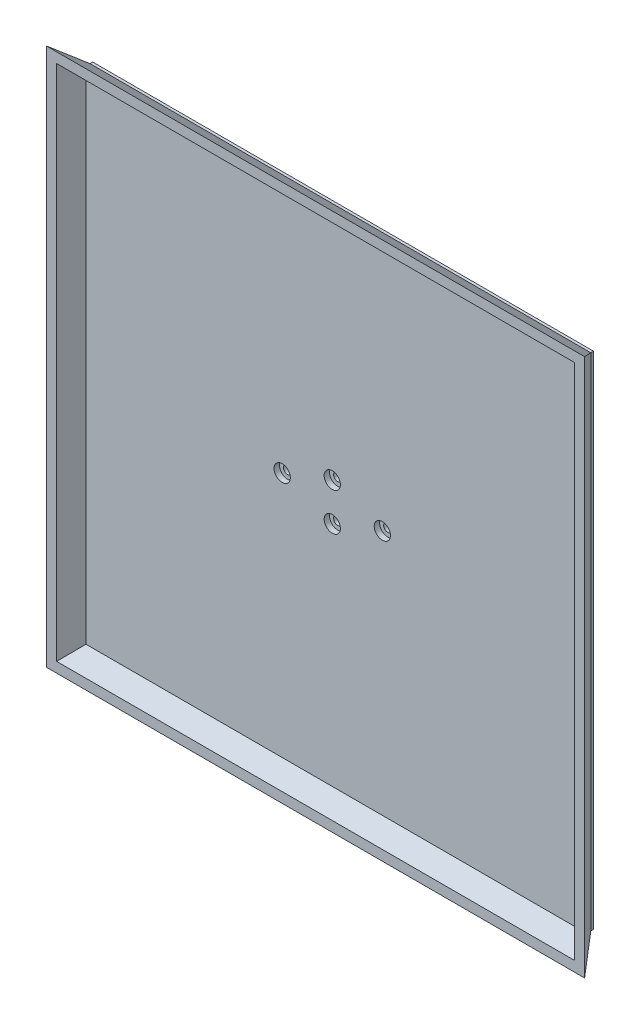
SolidWorks part; units mm, degrees
ref_plane "前视基准面" through (0, 0, 0) normal (0, 0, 1) x (1, 0, 0)
ref_plane "上视基准面" through (0, 0, 0) normal (0, 1, 0) x (1, 0, 0)
ref_plane "右视基准面" through (0, 0, 0) normal (1, 0, 0) x (0, 0, -1)
other "Configuration Table"
sketch "草图1" plane through (0, 0, 0) normal (0, 0, 1) x (1, 0, 0)
  line L11 (-17.5, -167.5) -> (167.5, -167.5)
  line L12 (-17.5, -167.5) -> (-17.5, 17.5)
  line L13 (-17.5, 17.5) -> (167.5, 17.5)
  line L14 (167.5, -167.5) -> (167.5, 17.5)
sketch "草图3" plane through (0, 0, 20) normal (0, 0, 1) x (1, 0, 0)
  line L7 (-32.4602, 32.2748) -> (182.5398, 32.2748)
  line L8 (-32.4602, 32.2748) -> (-32.4602, -182.7252)
  line L9 (-32.4602, -182.7252) -> (182.5398, -182.7252)
  line L10 (182.5398, 32.2748) -> (182.5398, -182.7252)
  point P12 (75.0398, -75.2252)
  dimension "D1" = 215
  dimension "D2" = 215
loft "放样1" add profiles "草图3", "草图1"
shell "抽壳2" thickness 3
sketch "草图4" plane through (0, 0, 3) normal (0, 0, 1) x (1, 0, 0)
  line L0 (75, 15.9864) -> (75, -182.7252)
  line L1 (166.0024, 15.9864) -> (-15.9976, 15.9864) construction
  line L2 (-32.4602, -182.7252) -> (182.5398, -182.7252) construction
  line L3 (-32.4602, -75.2252) -> (182.5398, -75.2252)
  line L4 (-32.4602, 32.2748) -> (-32.4602, -182.7252) construction
  line L5 (182.5398, -182.7252) -> (182.5398, 32.2748) construction
  circle A0 centre (66.25, -75.2252) radius 7 construction
  circle A1 centre (66.25, -75.2252) radius 4
  circle A2 centre (66.25, -68.2252) radius 1.5
  circle A3 centre (66.25, -82.2252) radius 1.5
  circle A4 centre (73.25, -75.2252) radius 1.5
  circle A5 centre (59.25, -75.2252) radius 1.5
  circle A6 centre (84.75, -75.2252) radius 1.5
  circle A7 centre (47.75, -75.2252) radius 1.5
  dimension "D1" = 8
  dimension "D2" = 14
  dimension "D3" = 3
  dimension "D4" = 3
  dimension "D5" = 3
  dimension "D6" = 3
  dimension "D7" = 3
  dimension "D8" = 3
  dimension "D9" = 37
  dimension "D10" = 18.5
extrude "切除-拉伸1" cut sketch "草图4" against normal blind 10 contours L3 A6 | L3 A6 | A3 | L3 A4 | L3 A4 | A2 | L3 A5 | L3 A5 | L3 A7 | L3 A7
sketch "草图6" plane through (0, 0, 3) normal (0, 0, 1) x (1, 0, 0)
  line L2 (38.15, -62.5) -> (34.15, -62.5)
  line L5 (38.15, -75) -> (38.15, -62.5)
  line L6 (38.15, -75) -> (38.15, -87.5)
  line L7 (94.35, -75) -> (94.35, -62.5)
  line L8 (94.35, -75) -> (94.35, -87.5)
  line L9 (94.35, -62.5) -> (98.35, -62.5)
  line L11 (98.35, -87.5) -> (94.35, -87.5)
  line L12 (98.35, -87.5) -> (101.35, -87.5)
  line L13 (101.35, -87.5) -> (101.35, -84.5)
  line L14 (98.35, -62.5) -> (101.35, -62.5)
  line L15 (101.35, -62.5) -> (101.35, -65.5)
  line L16 (38.15, -87.5) -> (34.15, -87.5)
  line L17 (34.15, -62.5) -> (31.15, -62.5)
  line L18 (31.15, -62.5) -> (31.15, -65.5)
  line L19 (34.15, -87.5) -> (31.15, -87.5)
  line L20 (31.15, -87.5) -> (31.15, -84.5)
  line L21 (31.15, -65.5) -> (34.15, -65.5)
  line L22 (31.15, -84.5) -> (34.15, -84.5)
  line L23 (34.15, -84.5) -> (34.15, -65.5)
  line L24 (101.35, -65.5) -> (98.35, -65.5)
  line L25 (101.35, -84.5) -> (98.35, -84.5)
  line L26 (98.35, -84.5) -> (98.35, -65.5)
extrude "凸台-拉伸1" add sketch "草图6" against normal blind 40.5
sketch "草图7" plane through (98.35, 0, 0) normal (1, 0, 0) x (0, 0, -1)
  line L0 (0, -65.5) -> (0, -84.5)
  line L1 (0, -75) -> (16.5, -75)
  line L2 (16.5, -75) -> (33.5, -75)
  line L3 (33.5, -75) -> (37.5, -75)
  line L4 (37.5, -84.5) -> (37.5, -65.5) construction
  circle A0 centre (16.5, -75) radius 1.51
  circle A1 centre (33.5, -75) radius 1.51
extrude "切除-拉伸2" cut sketch "草图7" against normal blind 100 contours L2 A0 L1 | L1 A0 L2 | L3 A1 L2 | L2 A1 L3
sketch "草图8" plane through (0, 0, 3) normal (0, 0, 1) x (1, 0, 0)
  circle A0 centre (66.25, -68.2252) radius 1.5
  circle A1 centre (59.25, -75.2252) radius 1.5
  circle A2 centre (47.75, -75.2252) radius 1.5
  circle A3 centre (73.25, -75.2252) radius 1.5
  circle A4 centre (84.75, -75.2252) radius 1.5
  circle A5 centre (66.25, -82.2252) radius 1.5
extrude "凸台-拉伸2" add sketch "草图8" against normal blind 3 contours A0
sketch "草图9" plane through (0, 0, 0) normal (0, 0, -1) x (-1, 0, 0)
  line L3 (-73.5858, -76.4142) -> (0, -2.8284)
  line L4 (17.5, 17.5) -> (17.5, -167.5) construction
  line L5 (0, -2.8284) -> (0, 0)
  line L6 (-72.7486, -69.9202) -> (-2.8284, 0)
  line L7 (-167.5, 17.5) -> (17.5, 17.5) construction
  line L8 (-2.8284, 0) -> (0, 0)
  line L9 (-72.7486, -69.9202) -> (-150, -147.1716)
  line L10 (-167.5, -167.5) -> (-167.5, 17.5) construction
  line L11 (-150, -147.1716) -> (-150, -150)
  line L12 (-73.5858, -76.4142) -> (-147.1716, -150)
  line L14 (17.5, -167.5) -> (-167.5, -167.5) construction
  line L15 (-147.1716, -150) -> (-150, -150)
extrude "凸台-拉伸3" add sketch "草图9" along normal blind 4 contours L9 L11 L15 L12 L3 L5 L8 L6
sketch "草图10" plane through (0, 0, 0) normal (0, 0, -1) x (-1, 0, 0)
  line L3 (-106.6693, -40.5023) -> (-147.1716, 17.5)
  line L4 (-167.5, 17.5) -> (17.5, 17.5) construction
  line L5 (-147.1716, 17.5) -> (-167.5, 17.5)
  line L6 (-121.9738, -30.8546) -> (-167.5, 34.3423)
  line L7 (-167.5, -167.5) -> (-167.5, 17.5) construction
  line L8 (-167.5, 34.3423) -> (-167.5, 17.5)
  line L9 (-106.6693, -40.5023) -> (17.5, -218.322)
  line L10 (17.5, 17.5) -> (17.5, -167.5) construction
  line L11 (17.5, -218.322) -> (17.5, -167.5)
  line L12 (-121.9738, -30.8546) -> (-26.556, -167.5)
  line L13 (17.5, -167.5) -> (-167.5, -167.5) construction
  line L14 (-26.556, -167.5) -> (17.5, -167.5)
extrude "凸台-拉伸4" add sketch "草图10" along normal blind 4 contours L3 L5 L8 L6 L12 L14 L11 L9
sketch "草图11" plane through (0, 0, -4) normal (0, 0, -1) x (-1, 0, 0)
  line L1 (-94.35, -62.5) -> (-38.15, -62.5)
  line L2 (-94.35, -62.5) -> (-94.35, -87.5)
  line L3 (-94.35, -87.5) -> (-38.15, -87.5)
  line L4 (-38.15, -62.5) -> (-38.15, -87.5)
extrude "切除-拉伸3" cut sketch "草图11" against normal blind 4 contours L2 L1 L4 L3
sketch "草图12" plane through (0, 0, 20) normal (0, 0, 1) x (1, 0, 0)
  line L1 (182.5398, 32.2748) -> (185.5398, 32.2748)
  line L2 (182.5398, 32.2748) -> (182.5398, -182.7252)
  line L3 (182.5398, -182.7252) -> (185.5398, -182.7252)
  line L4 (185.5398, 32.2748) -> (185.5398, -182.7252)
extrude "凸台-拉伸5" add sketch "草图12" against normal blind 10 separate body
sketch "草图13" plane through (185.5398, 0, 0) normal (1, 0, 0) x (0, 0, -1)
  line L0 (-10, -182.7252) -> (-10, 32.2748) construction
  line L1 (-20, 32.2748) -> (-10, 32.2748)
  line L2 (-20, 32.2748) -> (-20, -182.7252)
  line L3 (-20, -182.7252) -> (-10, -182.7252)
  line L4 (-10, 32.2748) -> (-10, -182.7252)
extrude "切除-拉伸4" cut sketch "草图13" against normal blind 300
sketch "草图15" plane through (0, 0, -4) normal (0, 0, -1) x (-1, 0, 0)
  line L1 (-154.8521, -152.6743) -> (-38.15, -152.6743)
  line L2 (-154.8521, -152.6743) -> (-154.8521, -87.5)
  line L3 (-154.8521, -87.5) -> (-38.15, -87.5)
  line L4 (-38.15, -152.6743) -> (-38.15, -87.5)
  line L5 (-94.35, -62.5) -> (17.5, -62.5)
  line L6 (-94.35, -62.5) -> (-94.35, 17.5)
  line L7 (-94.35, 17.5) -> (17.5, 17.5)
  line L8 (17.5, -62.5) -> (17.5, 17.5)
extrude "切除-拉伸5" cut sketch "草图15" against normal blind 4 contours L6 L5 L8 L7 | L2 L1 L4 L3
sketch "草图16" plane through (0, 0, 0) normal (0, 0, -1) x (-1, 0, 0)
  line L3 (-123.7693, -120.9409) -> (-167.5, -164.6716)
  line L4 (-134.8709, -12.3007) -> (-164.6716, 17.5)
  line L5 (-167.5, 17.5) -> (17.5, 17.5) construction
  line L6 (-164.6716, 17.5) -> (-167.5, 17.5)
  line L7 (-140.0326, -12.7959) -> (-167.5, 14.6716)
  line L8 (-167.5, -167.5) -> (-167.5, 17.5) construction
  line L9 (-167.5, 14.6716) -> (-167.5, 17.5)
  line L10 (-140.0326, -12.7959) -> (14.6716, -167.5)
  line L11 (17.5, -167.5) -> (-167.5, -167.5) construction
  line L12 (14.6716, -167.5) -> (17.5, -167.5)
  line L14 (-134.8709, -12.3007) -> (17.5, -164.6716)
  line L15 (17.5, 17.5) -> (17.5, -167.5) construction
  line L16 (17.5, -164.6716) -> (17.5, -167.5)
  line L17 (-167.5, -164.6716) -> (-167.5, -167.5)
  line L18 (-116.3532, -119.1816) -> (-164.6716, -167.5)
  line L19 (-164.6716, -167.5) -> (-167.5, -167.5)
  line L20 (-116.3532, -119.1816) -> (17.5, 14.6716)
  line L21 (17.5, 14.6716) -> (17.5, 17.5)
  line L22 (-123.7693, -120.9409) -> (14.6716, 17.5)
  line L23 (14.6716, 17.5) -> (17.5, 17.5)
extrude "凸台-拉伸6" add sketch "草图16" along normal blind 4
sketch "草图17" plane through (0, 0, 0) normal (0, 0, -1) x (-1, 0, 0)
  line L1 (-94.35, -62.5) -> (-38.15, -62.5)
  line L2 (-94.35, -62.5) -> (-94.35, -87.5)
  line L3 (-94.35, -87.5) -> (-38.15, -87.5)
  line L4 (-38.15, -62.5) -> (-38.15, -87.5)
extrude "切除-拉伸6" cut sketch "草图17" along normal blind 4 contours L2 L1 L4 L3
sketch "草图18" plane through (0, 0, 0) normal (0, 0, -1) x (-1, 0, 0)
  line L3 (-75, -119.25) -> (-33.5784, -119.25)
  line L7 (-65.3284, -87.5) -> (14.6716, -167.5) construction
  line L8 (-33.5784, -119.25) -> (-31.5784, -121.25)
  line L9 (-65.3284, -87.5) -> (14.6716, -167.5) construction
  line L10 (-75, -123.25) -> (-29.5784, -123.25)
  line L11 (-29.5784, -123.25) -> (-31.5784, -121.25)
  line L12 (-75, -119.25) -> (-116.4216, -119.25)
  line L13 (-164.6716, -167.5) -> (-84.6716, -87.5) construction
  line L14 (-75, -123.25) -> (-120.4216, -123.25)
  line L15 (-120.4216, -123.25) -> (-116.4216, -119.25)
  line L18 (-119.25, -75) -> (-119.25, -116.4216)
  line L19 (-90.3284, -87.5) -> (-167.5, -164.6716) construction
  line L20 (-119.25, -116.4216) -> (-121.25, -118.4216)
  line L21 (-123.25, -75) -> (-123.25, -120.4216)
  line L22 (-123.25, -120.4216) -> (-121.25, -118.4216)
  line L23 (-119.25, -75) -> (-119.25, -33.5784)
  line L24 (-167.5, 14.6716) -> (-90.3284, -62.5) construction
  line L25 (-123.25, -75) -> (-123.25, -29.5784)
  line L26 (-167.5, 14.6716) -> (-90.3284, -62.5) construction
  line L27 (-123.25, -29.5784) -> (-119.25, -33.5784)
  line L30 (-75, -30.75) -> (-116.4216, -30.75)
  line L31 (-164.6716, 17.5) -> (-84.6716, -62.5) construction
  line L32 (-75, -26.75) -> (-120.4216, -26.75)
  line L33 (-164.6716, 17.5) -> (-84.6716, -62.5) construction
  line L34 (-120.4216, -26.75) -> (-116.4216, -30.75)
  line L35 (-75, -30.75) -> (-33.5784, -30.75)
  line L36 (14.6716, 17.5) -> (-65.3284, -62.5) construction
  line L37 (-75, -26.75) -> (-29.5784, -26.75)
  line L38 (-65.3284, -62.5) -> (14.6716, 17.5) construction
  line L39 (-29.5784, -26.75) -> (-33.5784, -30.75)
  line L40 (-30.75, -33.5784) -> (-26.75, -29.5784)
  line L42 (-26.75, -75) -> (-26.75, -29.5784)
  line L43 (-59.6716, -62.5) -> (17.5, 14.6716) construction
  line L44 (-30.75, -75) -> (-30.75, -33.5784)
  line L45 (-30.75, -75) -> (-30.75, -116.4216)
  line L46 (-59.6716, -87.5) -> (17.5, -164.6716) construction
  line L47 (-26.75, -75) -> (-26.75, -120.4216)
  line L48 (-30.75, -116.4216) -> (-26.75, -120.4216)
extrude "凸台-拉伸7" add sketch "草图18" along normal blind 4
sketch "草图20" plane through (0, 0, 0) normal (0, 0, -1) x (-1, 0, 0)
  line L0 (-94.35, -62.5) -> (-94.35, -87.5)
  line L1 (-94.35, -87.5) -> (-38.15, -87.5)
  line L2 (-38.15, -87.5) -> (-38.15, -62.5)
  line L3 (-38.15, -62.5) -> (-94.35, -62.5)
  line L4 (-66.25, -75) -> (-66.25, -82)
  line L5 (-66.25, -75) -> (-47.75, -75)
  line L6 (-66.25, -75) -> (-84.75, -75)
  line L7 (-66.25, -75) -> (-66.25, -68)
  circle A0 centre (-84.75, -75) radius 1.5
  circle A1 centre (-47.75, -75) radius 1.5
  circle A2 centre (-66.25, -68) radius 1.5
  circle A3 centre (-66.25, -82) radius 1.5
extrude "切除-拉伸7" cut sketch "草图20" against normal blind 10
sketch "草图21" plane through (0, 0, -37.5) normal (0, 0, -1) x (-1, 0, 0)
  line L1 (-167.5, 17.5) -> (17.5, 17.5)
  line L2 (-167.5, 17.5) -> (-167.5, -167.5)
  line L3 (-167.5, -167.5) -> (17.5, -167.5)
  line L4 (17.5, 17.5) -> (17.5, -167.5)
extrude "切除-拉伸8" cut sketch "草图21" against normal blind 37.5
sketch "草图22" plane through (0, 0, 0) normal (0, 0, -1) x (-1, 0, 0)
  line L1 (17.5, 17.5) -> (-167.5, 17.5)
  line L2 (17.5, 17.5) -> (17.5, -167.5)
  line L3 (17.5, -167.5) -> (-167.5, -167.5)
  line L4 (-167.5, 17.5) -> (-167.5, -167.5)
  circle A0 centre (-66.25, -68) radius 1.5
  circle A1 centre (-66.25, -82) radius 1.5
  circle A2 centre (-84.75, -75) radius 1.5
  circle A3 centre (-47.75, -75) radius 1.5
extrude "凸台-拉伸8" add sketch "草图22" along normal blind 1 contours L2 L1 L4 L3 | A3 | A0 | A2 | A1
sketch "草图24" plane through (0, 0, 3) normal (0, 0, 1) x (1, 0, 0)
  circle A0 centre (66.25, -68) radius 3
  circle A1 centre (66.25, -82) radius 3
  circle A2 centre (47.75, -75) radius 3
  circle A3 centre (84.75, -75) radius 3
  circle M4 centre (66.25, -68) radius 1.5
  circle M5 centre (84.75, -75) radius 1.5
  circle M6 centre (66.25, -82) radius 1.5
extrude "切除-拉伸9" cut sketch "草图24" against normal blind 2 contours A0 M4 | A1 M6 | A3 M5 | A2
sketch "草图25" plane through (0, 0, -1) normal (0, 0, -1) x (-1, 0, 0)
  line L0 (-167.5, 17.5) -> (17.5, -167.5)
  line L1 (-75, -75) -> (-75, -68)
  line L2 (-75, -75) -> (-75, -82)
  line L4 (-75, -75) -> (-56.5, -75)
  line L5 (-75, -75) -> (-93.5, -75)
  circle A0 centre (-75, -68) radius 1.51
  circle A1 centre (-75, -82) radius 1.51
  circle A2 centre (-93.5, -75) radius 1.51
  circle A3 centre (-56.5, -75) radius 1.51
extrude "切除-拉伸10" cut sketch "草图25" against normal blind 10
sketch "草图26" plane through (0, 0, -1) normal (0, 0, -1) x (-1, 0, 0)
  circle A0 centre (-84.75, -75) radius 1.5
  circle A1 centre (-66.25, -68) radius 1.5
  circle A2 centre (-66.25, -82) radius 1.5
  circle A3 centre (-47.75, -75) radius 1.5
extrude "凸台-拉伸9" add sketch "草图26" against normal blind 4 contours A0 | A1 | A2 | A3
sketch "草图28" plane through (0, 0, 3) normal (0, 0, 1) x (1, 0, 0)
  circle A0 centre (84.75, -75) radius 3
  circle A1 centre (66.25, -68) radius 3
  circle A2 centre (47.75, -75) radius 3
  circle A3 centre (66.25, -82) radius 3
extrude "凸台-拉伸10" add sketch "草图28" against normal blind 4
sketch "草图29" plane through (0, 0, 3) normal (0, 0, 1) x (1, 0, 0)
  circle A0 centre (75, -68) radius 3
  circle A1 centre (75, -82) radius 3
  circle A2 centre (93.5, -75) radius 3
  circle A3 centre (56.5, -75) radius 3
extrude "切除-拉伸11" cut sketch "草图29" against normal blind 2
sketch "草图30" plane through (-11.2214, 0, -8.3937) normal (-0.8008, 0, -0.599) x (-0.599, 0, 0.8008)
  line L0 (22.9702, 23.2126) -> (21.9702, 23.2126)
  line L1 (22.9702, -175.1126) -> (22.9702, 24.8874) construction
  line L3 (21.9702, 23.2126) -> (22.9702, 23.2126)
  line L4 (21.9702, 23.2126) -> (21.9702, 25.5215)
  line L5 (21.9702, 25.5215) -> (22.9702, 25.5215)
  line L6 (22.9702, 23.2126) -> (22.9702, 25.5215)
  line L7 (21.9702, 23.2126) -> (24.4729, 23.2126)
  line L8 (21.9702, 23.2126) -> (21.9702, -177.3761)
  line L9 (21.9702, -177.3761) -> (24.4729, -177.3761)
  line L10 (24.4729, 23.2126) -> (24.4729, -177.3761)
  line M2 (10.4822, -167.5) -> (22.9702, -175.1126)
  line M3 (22.9702, -175.1126) -> (22.9702, 24.8874)
  line M4 (22.9702, 24.8874) -> (10.4822, 17.5)
extrude "切除-拉伸12" cut sketch "草图30" against normal blind 10 contours L6 L5 L4 M4 | L4 L0 M3 M4 | L0 L8 M2 M3 | L10 L7 L8 L9 M3 M2
sketch "草图31" plane through (0, 11.3215, -8.3636) normal (0, 0.8043, -0.5942) x (1, 0, 0)
  line L0 (-9.3628, -22.831) -> (-9.3628, -21.831)
  line L1 (-23.3106, -22.831) -> (175.0199, -22.831) construction
  line L3 (-9.3628, -21.831) -> (-28.9973, -21.831)
  line L4 (-9.3628, -21.831) -> (-9.3628, -26.3658)
  line L5 (-9.3628, -26.3658) -> (-28.9973, -26.3658)
  line L6 (-28.9973, -21.831) -> (-28.9973, -26.3658)
  line L7 (-9.3628, -21.831) -> (184.8283, -21.831)
  line L8 (-9.3628, -21.831) -> (-9.3628, -29.9137)
  line L9 (-9.3628, -29.9137) -> (184.8283, -29.9137)
  line L10 (184.8283, -21.831) -> (184.8283, -29.9137)
  line M2 (-24.3811, -21.8355) -> (-23.3106, -22.831)
  line M3 (-23.3106, -22.831) -> (175.0199, -22.831)
  line M4 (175.0199, -22.831) -> (167.5, -10.3983)
  line M8 (-17.5, -10.3983) -> (-24.3811, -21.8355)
extrude "切除-拉伸13" cut sketch "草图31" against normal blind 10 contours L3 L6 L5 L4 M3 M2 M8 | L10 L7 L4 L8 L9 M4 M3 | L0 L3 M8 M2 M3 | L7 L0 M3 M4
sketch "草图32" plane through (106.9956, 0, -80.4593) normal (0.7992, 0, -0.601) x (-0.601, 0, -0.7992)
  line L0 (-113.1822, -69.7237) -> (-112.1822, -69.7237)
  line L1 (-113.1822, 23.2044) -> (-113.1822, -175.1126) construction
  line L3 (-112.1822, -69.7237) -> (-120.0099, -69.7237)
  line L4 (-112.1822, -69.7237) -> (-112.1822, 28.1473)
  line L5 (-112.1822, 28.1473) -> (-120.0099, 28.1473)
  line L6 (-120.0099, -69.7237) -> (-120.0099, 28.1473)
  line L7 (-112.1822, -69.7237) -> (-120.0099, -69.7237)
  line L8 (-112.1822, -69.7237) -> (-112.1822, -178.2761)
  line L9 (-112.1822, -178.2761) -> (-120.0099, -178.2761)
  line L10 (-120.0099, -69.7237) -> (-120.0099, -178.2761)
  line M3 (-112.1758, 24.2932) -> (-113.1822, 23.2044)
  line M4 (-113.1822, 23.2044) -> (-113.1822, -175.1126)
  line M5 (-113.1822, -175.1126) -> (-100.6702, -167.5)
extrude "切除-拉伸14" cut sketch "草图32" against normal blind 10 contours L6 L3 L4 L5 M4 M3 | L0 L4 M3 M4 | L3 L10 L9 L8 M5 M4 | L8 L0 M4 M5
sketch "草图33" plane through (0, -106.0449, -80.7279) normal (0, -0.7957, -0.6057) x (1, 0, 0)
  line L0 (69.3935, 114.0259) -> (69.3935, 113.0259)
  line L1 (173.356, 114.0259) -> (-23.3106, 114.0259) construction
  line L3 (69.3935, 113.0259) -> (179.7251, 113.0259)
  line L4 (69.3935, 113.0259) -> (69.3935, 118.677)
  line L5 (69.3935, 118.677) -> (179.7251, 118.677)
  line L6 (179.7251, 113.0259) -> (179.7251, 118.677)
  line L7 (69.3935, 113.0259) -> (-31.9687, 113.0259)
  line L8 (69.3935, 113.0259) -> (69.3935, 127.9963)
  line L9 (69.3935, 127.9963) -> (-31.9687, 127.9963)
  line L10 (-31.9687, 113.0259) -> (-31.9687, 127.9963)
  line M7 (174.4189, 113.0215) -> (173.356, 114.0259)
  line M8 (173.356, 114.0259) -> (-23.3106, 114.0259)
  line M9 (-23.3106, 114.0259) -> (-24.3811, 113.0196)
extrude "切除-拉伸15" cut sketch "草图33" against normal blind 10 contours L3 L6 L5 L4 M8 M7 | L10 L7 L4 L8 L9 M9 M8 | L7 L0 M8 M9 | L0 L3 M7 M8
sketch "草图36" plane through (-17.5, 0, 0) normal (-1, 0, 0) x (0, 0, 1)
  line L0 (10, 23.2044) -> (9.19, 23.2044)
  line L3 (9.19, 23.2044) -> (10.0434, 23.2044)
  line L4 (9.19, 23.2044) -> (9.19, 24.4576)
  line L5 (9.19, 24.4576) -> (10.0434, 24.4576)
  line L6 (10.0434, 23.2044) -> (10.0434, 24.4576)
  line L7 (9.19, 23.2044) -> (10.8591, 23.2044)
  line L8 (9.19, 23.2044) -> (9.19, -174.8077)
  line L9 (9.19, -174.8077) -> (10.8591, -174.8077)
  line L10 (10.8591, 23.2044) -> (10.8591, -174.8077)
extrude "切除-拉伸19" cut sketch "草图36" against normal blind 200 contours L10 L7 L3 L0 L8 L9 | L3 L6 L5 L4 L0
sketch "草图37" plane through (-17.5, 0, 0) normal (1, 0, 0) x (0, 0, -1)
  line L0 (-10, -173.4617) -> (-9.19, -173.4617)
  line L1 (-9.19, -170.7256) -> (-9.19, -174.496) construction
  line L3 (-9.19, -173.4617) -> (-10.1205, -173.4617)
  line L4 (-9.19, -173.4617) -> (-9.19, 24.4224)
  line L5 (-9.19, 24.4224) -> (-10.1205, 24.4224)
  line L6 (-10.1205, -173.4617) -> (-10.1205, 24.4224)
  line L7 (-10.1205, -173.4617) -> (-9.19, -173.4617)
  line L8 (-10.1205, -173.4617) -> (-10.1205, -174.6376)
  line L9 (-10.1205, -174.6376) -> (-9.19, -174.6376)
  line L10 (-9.19, -173.4617) -> (-9.19, -174.6376)
  line M1 (-9.19, -170.7256) -> (-10, -171.3423)
  line M2 (-10, -171.3423) -> (-10, -173.4617)
  line M3 (-10, -173.4617) -> (-9.2043, -174.5069)
  line M4 (-9.2043, -174.5069) -> (-9.19, -174.496)
  line M5 (-9.19, -174.496) -> (-9.19, -170.7256)
extrude "切除-拉伸20" cut sketch "草图37" against normal blind 200 contours L10 L3 L8 L9 M4 M3 | L0 M3 M4 M5 | L0 M2 M5 M1 | L6 L3 L4 L5 M2 M1
